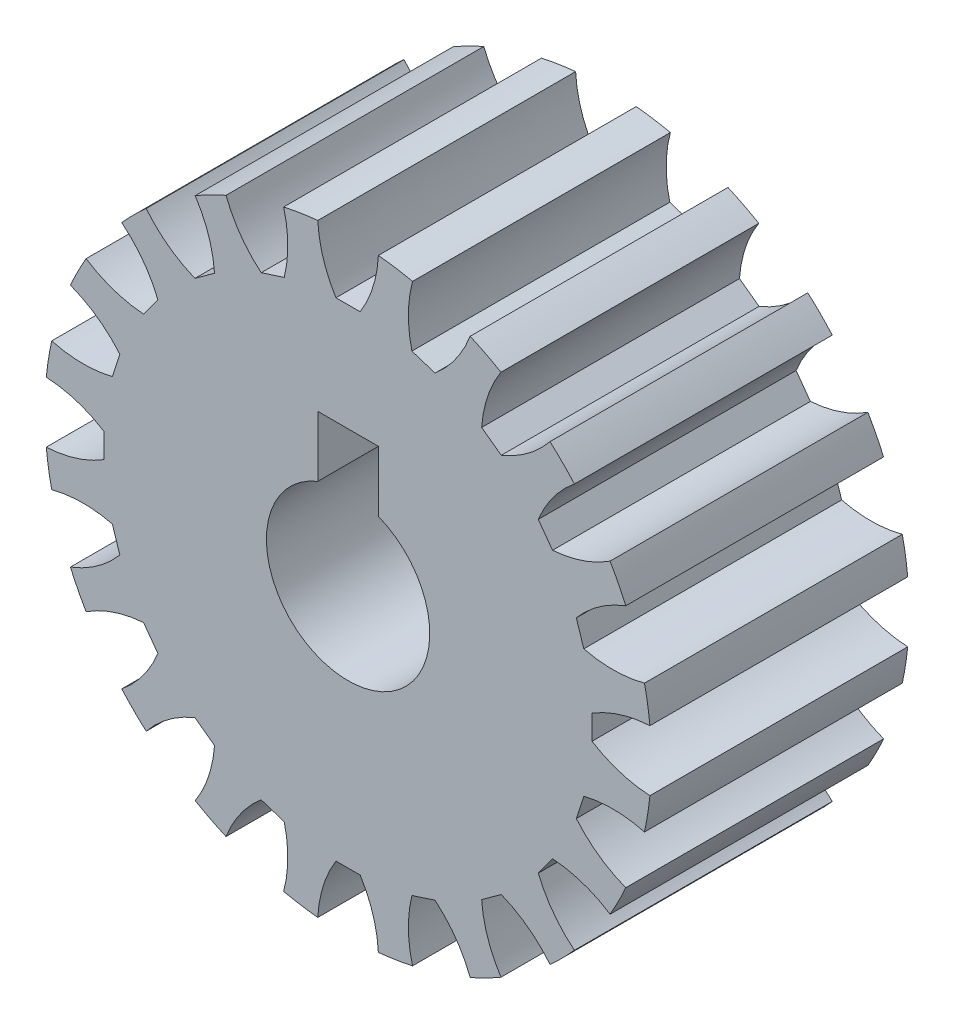
SolidWorks part; units mm, degrees
ref_plane "Front Plane" through (0, 0, 0) normal (0, 0, 1) x (1, 0, 0)
ref_plane "Top Plane" through (0, 0, 0) normal (0, 1, 0) x (1, 0, 0)
ref_plane "Right Plane" through (0, 0, 0) normal (1, 0, 0) x (0, 0, -1)
sketch "Sketch1" plane through (0, 0, 0) normal (0, 0, 1) x (1, 0, 0)
  circle A0 centre (0, 0) radius 100
  dimension "D1" = 200
extrude "Boss-Extrude1" add sketch "Sketch1" along normal blind 85 contours A0
sketch "Sketch2" plane through (0, 0, 85) normal (0, 0, 1) x (1, 0, 0)
  line L0 (0, 45) -> (0, 100) construction
  line L2 (0, 45) -> (-10, 45)
  line L3 (-10, 45) -> (-10, 25)
  line L4 (0, 45) -> (10, 45)
  line L5 (10, 45) -> (10, 25)
  arc A0 (-10, 25) -> (10, 25) centre (0, 0) ccw
  circle A1 centre (0, 0) radius 100 construction
  dimension "D1" = 20
  dimension "D2" = 10
  dimension "D3" = 10
  dimension "D4" = 20
extrude "Cut-Extrude2" cut sketch "Sketch2" against normal blind 85
sketch "Sketch3" plane through (0, 0, 0) normal (0, 0, 1) x (1, 0, 0)
  line L0 (0, 0) -> (0, 131.7199) construction
  line L4 (4, 80.4128) -> (-4, 80.4128)
  line L5 (28.6532, 75.2411) -> (21.0447, 77.7132)
  line L6 (50.5015, 62.7042) -> (44.0294, 67.4065)
  line L7 (67.4065, 44.0294) -> (62.7042, 50.5015)
  line L8 (77.7132, 21.0447) -> (75.2411, 28.6532)
  line L9 (80.4128, -4) -> (80.4128, 4)
  line L10 (75.2411, -28.6532) -> (77.7132, -21.0447)
  line L11 (62.7042, -50.5015) -> (67.4065, -44.0294)
  line L12 (44.0294, -67.4065) -> (50.5015, -62.7042)
  line L13 (21.0447, -77.7132) -> (28.6532, -75.2411)
  line L14 (-4, -80.4128) -> (4, -80.4128)
  line L15 (-28.6532, -75.2411) -> (-21.0447, -77.7132)
  line L16 (-50.5015, -62.7042) -> (-44.0294, -67.4065)
  line L17 (-67.4065, -44.0294) -> (-62.7042, -50.5015)
  line L18 (-77.7132, -21.0447) -> (-75.2411, -28.6532)
  line L19 (-80.4128, 4) -> (-80.4128, -4)
  line L20 (-75.2411, 28.6532) -> (-77.7132, 21.0447)
  line L21 (-62.7042, 50.5015) -> (-67.4065, 44.0294)
  line L22 (-44.0294, 67.4065) -> (-50.5015, 62.7042)
  line L23 (-21.0447, 77.7132) -> (-28.6532, 75.2411)
  line L24 (0, 0) -> (4, 80.4128) construction
  circle A0 centre (0, 0) radius 100 construction
  arc A3 (-9.9875, 99.5) -> (-4, 80.4128) centre (29.7755, 101.4906) ccw
  arc A4 (9.9875, 99.5) -> (4, 80.4128) centre (-29.7755, 101.4906) cw
  arc A5 (-9.9875, 99.5) -> (9.9875, 99.5) centre (0, 100) cw
  arc A6 (21.2485, 97.7164) -> (40.2459, 91.5438) centre (30.9017, 95.1057) cw
  arc A7 (40.2459, 91.5438) -> (28.6532, 75.2411) centre (3.0441, 105.7245) cw
  arc A8 (21.2485, 97.7164) -> (21.0447, 77.7132) centre (59.6806, 87.3222) ccw
  arc A9 (50.4046, 86.3677) -> (66.5647, 74.6267) centre (58.7785, 80.9017) cw
  arc A10 (66.5647, 74.6267) -> (50.5015, 62.7042) centre (35.5658, 99.6093) cw
  arc A11 (50.4046, 86.3677) -> (44.0294, 67.4065) centre (83.7436, 64.606) ccw
  arc A12 (74.6267, 66.5647) -> (86.3677, 50.4046) centre (80.9017, 58.7785) cw
  arc A13 (86.3677, 50.4046) -> (67.4065, 44.0294) centre (64.606, 83.7436) cw
  arc A14 (74.6267, 66.5647) -> (62.7042, 50.5015) centre (99.6093, 35.5658) ccw
  arc A15 (91.5438, 40.2459) -> (97.7164, 21.2485) centre (95.1057, 30.9017) cw
  arc A16 (97.7164, 21.2485) -> (77.7132, 21.0447) centre (87.3222, 59.6806) cw
  arc A17 (91.5438, 40.2459) -> (75.2411, 28.6532) centre (105.7245, 3.0441) ccw
  arc A18 (99.5, 9.9875) -> (99.5, -9.9875) centre (100, 0) cw
  arc A19 (99.5, -9.9875) -> (80.4128, -4) centre (101.4906, 29.7755) cw
  arc A20 (99.5, 9.9875) -> (80.4128, 4) centre (101.4906, -29.7755) ccw
  arc A21 (97.7164, -21.2485) -> (91.5438, -40.2459) centre (95.1057, -30.9017) cw
  arc A22 (91.5438, -40.2459) -> (75.2411, -28.6532) centre (105.7245, -3.0441) cw
  arc A23 (97.7164, -21.2485) -> (77.7132, -21.0447) centre (87.3222, -59.6806) ccw
  arc A24 (86.3677, -50.4046) -> (74.6267, -66.5647) centre (80.9017, -58.7785) cw
  arc A25 (74.6267, -66.5647) -> (62.7042, -50.5015) centre (99.6093, -35.5658) cw
  arc A26 (86.3677, -50.4046) -> (67.4065, -44.0294) centre (64.606, -83.7436) ccw
  arc A27 (66.5647, -74.6267) -> (50.4046, -86.3677) centre (58.7785, -80.9017) cw
  arc A28 (50.4046, -86.3677) -> (44.0294, -67.4065) centre (83.7436, -64.606) cw
  arc A29 (66.5647, -74.6267) -> (50.5015, -62.7042) centre (35.5658, -99.6093) ccw
  arc A30 (40.2459, -91.5438) -> (21.2485, -97.7164) centre (30.9017, -95.1057) cw
  arc A31 (21.2485, -97.7164) -> (21.0447, -77.7132) centre (59.6806, -87.3222) cw
  arc A32 (40.2459, -91.5438) -> (28.6532, -75.2411) centre (3.0441, -105.7245) ccw
  arc A33 (9.9875, -99.5) -> (-9.9875, -99.5) centre (0, -100) cw
  arc A34 (-9.9875, -99.5) -> (-4, -80.4128) centre (29.7755, -101.4906) cw
  arc A35 (9.9875, -99.5) -> (4, -80.4128) centre (-29.7755, -101.4906) ccw
  arc A36 (-21.2485, -97.7164) -> (-40.2459, -91.5438) centre (-30.9017, -95.1057) cw
  arc A37 (-40.2459, -91.5438) -> (-28.6532, -75.2411) centre (-3.0441, -105.7245) cw
  arc A38 (-21.2485, -97.7164) -> (-21.0447, -77.7132) centre (-59.6806, -87.3222) ccw
  arc A39 (-50.4046, -86.3677) -> (-66.5647, -74.6267) centre (-58.7785, -80.9017) cw
  arc A40 (-66.5647, -74.6267) -> (-50.5015, -62.7042) centre (-35.5658, -99.6093) cw
  arc A41 (-50.4046, -86.3677) -> (-44.0294, -67.4065) centre (-83.7436, -64.606) ccw
  arc A42 (-74.6267, -66.5647) -> (-86.3677, -50.4046) centre (-80.9017, -58.7785) cw
  arc A43 (-86.3677, -50.4046) -> (-67.4065, -44.0294) centre (-64.606, -83.7436) cw
  arc A44 (-74.6267, -66.5647) -> (-62.7042, -50.5015) centre (-99.6093, -35.5658) ccw
  arc A45 (-91.5438, -40.2459) -> (-97.7164, -21.2485) centre (-95.1057, -30.9017) cw
  arc A46 (-97.7164, -21.2485) -> (-77.7132, -21.0447) centre (-87.3222, -59.6806) cw
  arc A47 (-91.5438, -40.2459) -> (-75.2411, -28.6532) centre (-105.7245, -3.0441) ccw
  arc A48 (-99.5, -9.9875) -> (-99.5, 9.9875) centre (-100, 0) cw
  arc A49 (-99.5, 9.9875) -> (-80.4128, 4) centre (-101.4906, -29.7755) cw
  arc A50 (-99.5, -9.9875) -> (-80.4128, -4) centre (-101.4906, 29.7755) ccw
  arc A51 (-97.7164, 21.2485) -> (-91.5438, 40.2459) centre (-95.1057, 30.9017) cw
  arc A52 (-91.5438, 40.2459) -> (-75.2411, 28.6532) centre (-105.7245, 3.0441) cw
  arc A53 (-97.7164, 21.2485) -> (-77.7132, 21.0447) centre (-87.3222, 59.6806) ccw
  arc A54 (-86.3677, 50.4046) -> (-74.6267, 66.5647) centre (-80.9017, 58.7785) cw
  arc A55 (-74.6267, 66.5647) -> (-62.7042, 50.5015) centre (-99.6093, 35.5658) cw
  arc A56 (-86.3677, 50.4046) -> (-67.4065, 44.0294) centre (-64.606, 83.7436) ccw
  arc A57 (-66.5647, 74.6267) -> (-50.4046, 86.3677) centre (-58.7785, 80.9017) cw
  arc A58 (-50.4046, 86.3677) -> (-44.0294, 67.4065) centre (-83.7436, 64.606) cw
  arc A59 (-66.5647, 74.6267) -> (-50.5015, 62.7042) centre (-35.5658, 99.6093) ccw
  arc A60 (-40.2459, 91.5438) -> (-21.2485, 97.7164) centre (-30.9017, 95.1057) cw
  arc A61 (-21.2485, 97.7164) -> (-21.0447, 77.7132) centre (-59.6806, 87.3222) cw
  arc A62 (-40.2459, 91.5438) -> (-28.6532, 75.2411) centre (-3.0441, 105.7245) ccw
  point P9 (0, 80.4128)
  point P12 (0, 80.4128)
  dimension "D2" = 80.5123
  dimension "D1" = 20
  dimension "D3" = 17.2572
extrude "Cut-Extrude17" cut sketch "Sketch3" along normal blind 144
